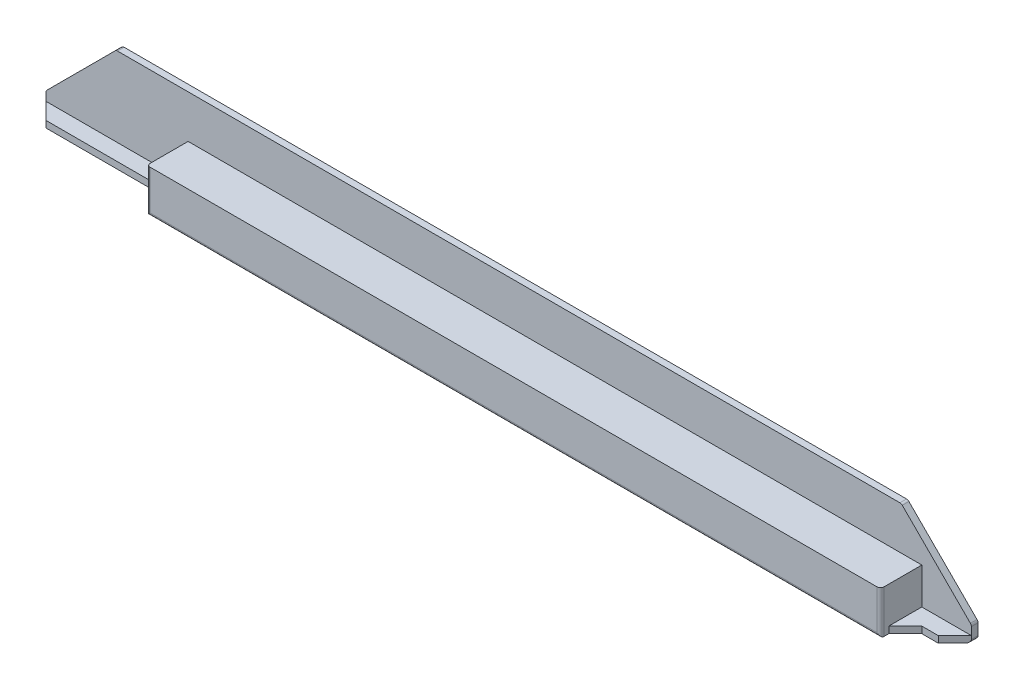
SolidWorks part; units mm, degrees
ref_plane "Front Plane" through (0, 0, 0) normal (0, 0, 1) x (1, 0, 0)
ref_plane "Top Plane" through (0, 0, 0) normal (0, 1, 0) x (1, 0, 0)
ref_plane "Right Plane" through (0, 0, 0) normal (1, 0, 0) x (0, 0, -1)
sketch "Sketch1" plane through (0, 0, 0) normal (0, 0, 1) x (1, 0, 0)
  line L0 (0, 2.7868) -> (21.2132, 24)
  line L1 (0, 0) -> (280, 0)
  line L2 (0, 0) -> (0, 24)
  line L3 (0, 24) -> (280, 24)
  line L4 (280, 0) -> (280, 24)
  line L5 (42, 0) -> (266, 0)
  line L6 (42, 0) -> (42, 11)
  line L7 (46, 15) -> (262, 15)
  line L8 (266, 0) -> (266, 11)
  line L9 (280, 2.7868) -> (258.7868, 24)
  arc A0 (262, 15) -> (266, 11) centre (262, 11) cw
  arc A1 (42, 11) -> (46, 15) centre (46, 11) cw
  dimension "D3" = 4
  dimension "D1" = 45
  dimension "D2" = 45
  dimension "D4" = 224
  dimension "D5" = 15
  dimension "D6" = 280
  dimension "D7" = 30
  dimension "D8" = 30
  dimension "D9" = 24
  dimension "D10" = 42
extrude "Boss-Extrude1" add sketch "Sketch1" along normal blind 2 contours L6 A1 L7 A0 L8 L1 L4 L9 L3 L0 L2 | A1 L6 L1 L8 A0 L7
sketch "Sketch2" plane through (0, 0, 0) normal (0, 0, 1) x (1, 0, 0)
  line L0 (46, 15) -> (262, 15) construction
  line L1 (62.01, 3.3) -> (65.99, 3.3)
  line L2 (62.01, 3.3) -> (62.01, 5)
  line L3 (62.01, 5) -> (65.99, 5)
  line L4 (65.99, 3.3) -> (65.99, 5)
  line L5 (46, 3.3) -> (58.4, 3.3)
  line L6 (46, 3.3) -> (46, 9.05)
  line L7 (46, 9.05) -> (58.4, 9.05)
  line L8 (58.4, 3.3) -> (58.4, 9.05)
  line L9 (82.01, 3.3) -> (85.99, 3.3)
  line L10 (82.01, 3.3) -> (82.01, 5)
  line L11 (82.01, 5) -> (85.99, 5)
  line L12 (85.99, 3.3) -> (85.99, 5)
  line L13 (102.01, 3.3) -> (105.99, 3.3)
  line L14 (102.01, 3.3) -> (102.01, 5)
  line L15 (102.01, 5) -> (105.99, 5)
  line L16 (105.99, 3.3) -> (105.99, 5)
  line L17 (122.01, 3.3) -> (125.99, 3.3)
  line L18 (122.01, 3.3) -> (122.01, 5)
  line L19 (122.01, 5) -> (125.99, 5)
  line L20 (125.99, 3.3) -> (125.99, 5)
  line L21 (142.01, 3.3) -> (145.99, 3.3)
  line L22 (142.01, 3.3) -> (142.01, 5)
  line L23 (142.01, 5) -> (145.99, 5)
  line L24 (145.99, 3.3) -> (145.99, 5)
  line L25 (162.01, 3.3) -> (165.99, 3.3)
  line L26 (162.01, 3.3) -> (162.01, 5)
  line L27 (162.01, 5) -> (165.99, 5)
  line L28 (165.99, 3.3) -> (165.99, 5)
  line L29 (182.01, 3.3) -> (185.99, 3.3)
  line L30 (182.01, 3.3) -> (182.01, 5)
  line L31 (182.01, 5) -> (185.99, 5)
  line L32 (185.99, 3.3) -> (185.99, 5)
  line L33 (202.01, 3.3) -> (205.99, 3.3)
  line L34 (202.01, 3.3) -> (202.01, 5)
  line L35 (202.01, 5) -> (205.99, 5)
  line L36 (205.99, 3.3) -> (205.99, 5)
  line L37 (222.01, 3.3) -> (225.99, 3.3)
  line L38 (222.01, 3.3) -> (222.01, 5)
  line L39 (222.01, 5) -> (225.99, 5)
  line L40 (225.99, 3.3) -> (225.99, 5)
  line L41 (242.01, 3.3) -> (245.99, 3.3)
  line L42 (242.01, 3.3) -> (242.01, 5)
  line L43 (242.01, 5) -> (245.99, 5)
  line L44 (245.99, 3.3) -> (245.99, 5)
  line L45 (62.01, 3.3) -> (82.01, 3.3) construction
  line L46 (145.99, 3.3) -> (162.01, 3.3)
  line L47 (249.6, 3.3) -> (262, 3.3)
  line L48 (249.6, 3.3) -> (249.6, 9.05)
  line L49 (249.6, 9.05) -> (262, 9.05)
  line L50 (262, 3.3) -> (262, 9.05)
  line L51 (42, 0) -> (42, 11) construction
  line L52 (266, 0) -> (266, 11) construction
  point P10 (154, 3.3)
  point P49 (154, 15)
  dimension "D1" = 3.98
  dimension "D2" = 1.7
  dimension "D3" = 12.4
  dimension "D4" = 5.75
  dimension "D5" = 10
  dimension "D7" = 20
  dimension "D8" = 12.4
  dimension "D9" = 5.75
  dimension "D10" = 4
  dimension "D11" = 4
  dimension "D6" = 10
sketch "Sketch10" plane through (0, 0, 0) normal (0, -1, 0) x (1, 0, 0)
  line L0 (280, 2) -> (280, 0) construction
  line L1 (0, 0) -> (280, 0)
  line L2 (0, 0) -> (0, 7)
  line L3 (0, 7) -> (280, 7)
  line L4 (280, 0) -> (280, 7)
  line L5 (0, 2) -> (280, 2) construction
  dimension "D1" = 5
extrude "Boss-Extrude3" add sketch "Sketch10" along normal blind 2
sketch "Sketch3" plane through (0, 0, 2) normal (0, 0, 1) x (1, 0, 0)
  line L0 (46, 15) -> (262, 15) construction
  line L1 (43, 11) -> (265, 11)
  line L2 (43, 11) -> (43, -2)
  line L3 (43, -2) -> (265, -2)
  line L4 (265, 11) -> (265, -2)
  line L5 (266, 0) -> (266, 11) construction
  line L6 (42, 0) -> (42, 11) construction
  line L8 (280, -2) -> (0, -2) construction
  dimension "D1" = 4
  dimension "D2" = 1
  dimension "D3" = 1
extrude "Boss-Extrude4" add sketch "Sketch3" along normal blind 12.5
chamfer "Chamfer1" distance 5 angle 45 4 edges at (43, -1, 7) (0, -1, 7) (280, -1, 7) (265, -1, 7)
fillet "Fillet1" radius 1 9 edges at (43, 4.5, 14.5) (265, 4.5, 14.5) (154, -2, 14.5) (258.7868, 24, 1) (280, 2.7868, 1) (280, -2, 1) (0, 2.7868, 1) (21.2132, 24, 1) (0, -2, 1)
